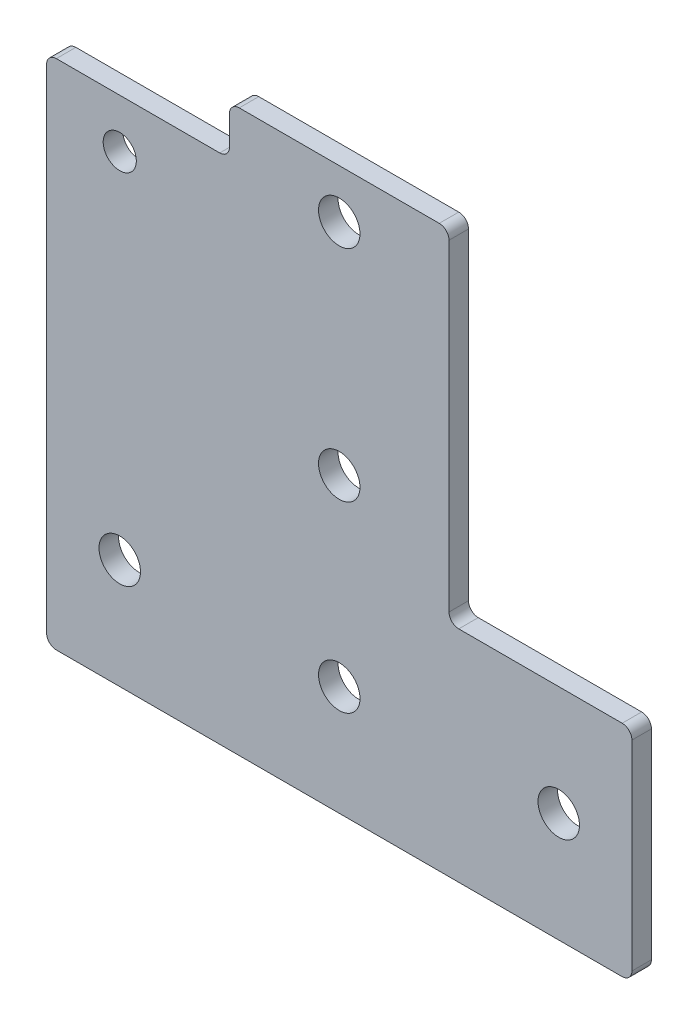
SolidWorks part; units mm, degrees
ref_plane "Front" through (0, 0, 0) normal (0, 0, 1) x (1, 0, 0)
ref_plane "Top" through (0, 0, 0) normal (0, 1, 0) x (1, 0, 0)
ref_plane "Right" through (0, 0, 0) normal (1, 0, 0) x (0, 0, -1)
sketch "Sketch1" plane through (0, 0, 0) normal (0, 0, 1) x (1, 0, 0)
  line L0 (0, 115) -> (0, 0) construction
  line L1 (-60, 0) -> (60, 0)
  line L2 (-60, 0) -> (-60, 45)
  line L4 (60, 0) -> (60, 45)
  line L6 (-22.5, 105) -> (-22.5, 115)
  line L7 (-22.5, 115) -> (22.5, 115)
  line L8 (22.5, 45) -> (22.5, 115)
  line L9 (22.5, 45) -> (60, 45)
  line L12 (-60, 45) -> (-60, 105)
  line L13 (-60, 105) -> (-22.5, 105)
  circle A0 centre (0, 22.5) radius 4.25
  circle A1 centre (-45, 22.5) radius 4.25
  circle A2 centre (45, 22.5) radius 4.25
  circle A3 centre (0, 105) radius 4.25
  circle A4 centre (0, 60) radius 4.25
  circle A5 centre (-45, 95) radius 3.4
  point P4 (-22.5, 45)
  point P8 (22.5, 45)
  dimension "D5" = 8.5
  dimension "D13" = 6.8
  dimension "D1" = 120
  dimension "D2" = 45
  dimension "D3" = 45
  dimension "D4" = 70
  dimension "D7" = 10
  dimension "D6" = 10
  dimension "D9" = 45
  dimension "D10" = 22.5
  dimension "D11" = 45
  dimension "D12" = 45
  dimension "D8" = 45
  dimension "D14" = 20
  dimension "D15" = 22.5
extrude "Boss-Extrude1" add sketch "Sketch1" along normal blind 4
fillet "Fillet1" radius 2 8 edges at (-60, 0, 2) (-22.5, 115, 2) (22.5, 115, 2) (60, 45, 2) (60, 0, 2) (22.5, 45, 2) (-60, 105, 2) (-22.5, 105, 2)
